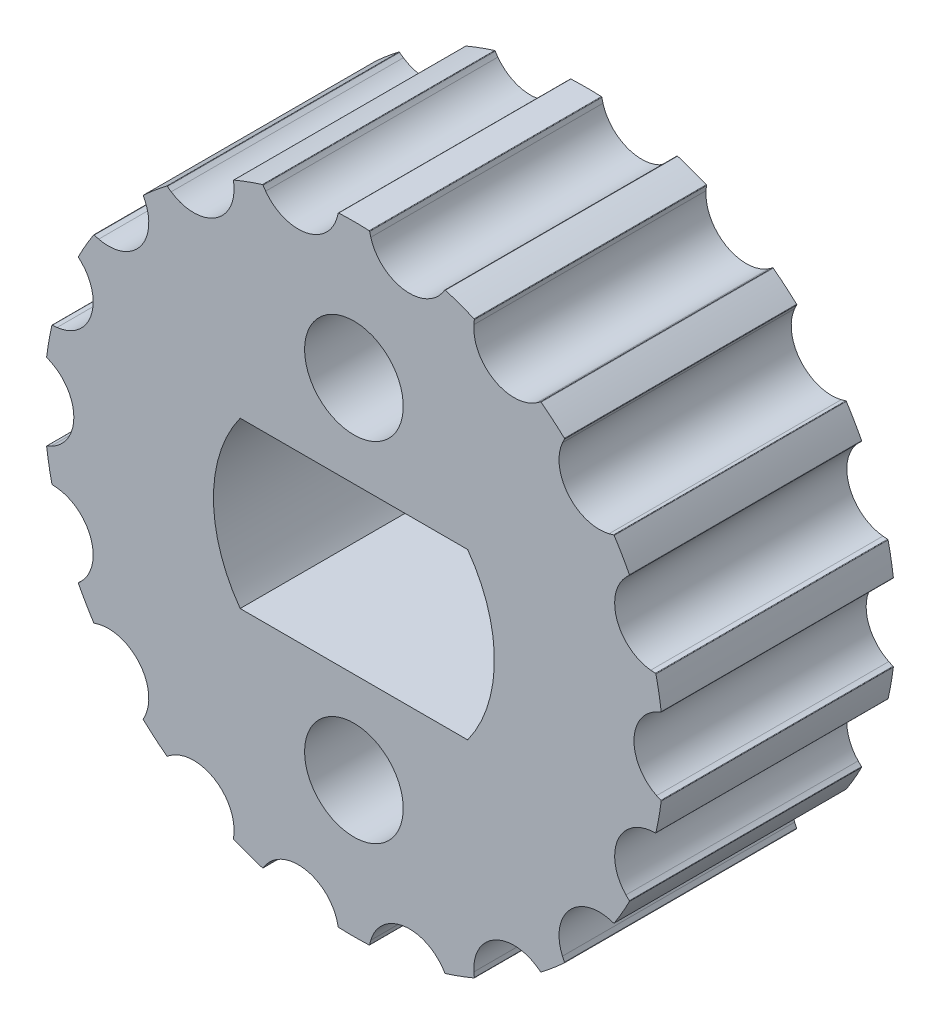
SolidWorks part; units mm, degrees
ref_plane "Face" through (0, 0, 0) normal (0, 0, 1) x (1, 0, 0)
ref_plane "Dessus" through (0, 0, 0) normal (0, 1, 0) x (1, 0, 0)
ref_plane "Droite" through (0, 0, 0) normal (1, 0, 0) x (0, 0, -1)
sketch "Esquisse1" plane through (0, 0, 0) normal (0, 0, 1) x (1, 0, 0)
  line L0 (0, 0) -> (-0.9949, 5.6425) construction
  line L1 (0, 0) -> (0.9949, 5.6425) construction
  line L2 (-1.1018, 6.2486) -> (-0.9949, 5.6425) construction
  line L3 (1.1018, 6.2486) -> (0.9949, 5.6425) construction
  line L4 (-1.3861, 5.5594) -> (0, 0) construction
  line L5 (0, 0) -> (0, 6.345) construction
  line L6 (-0.8378, 4.7517) -> (0, 0)
  line L7 (0, 0) -> (0.8378, 4.7517)
  arc A0 (-0.9949, 5.6425) -> (0.9949, 5.6425) centre (0, 0) cw construction
  arc A1 (1.1018, 6.2486) -> (-1.1018, 6.2486) centre (0, 0) ccw construction
  arc A2 (0.9508, 5.3924) -> (-0.9508, 5.3924) centre (0, 0) ccw construction
  arc A3 (-0.9949, 5.6425) -> (-1.3861, 5.5594) centre (0, 0) ccw construction
  arc A4 (-0.9508, 5.3924) -> (-1.3247, 5.3129) centre (0, 0) ccw construction
  arc A5 (-0.8622, 4.8895) -> (-0.4253, 5.2823) centre (-0.9585, 5.4361) ccw construction
  arc A6 (-0.4253, 5.2823) -> (-0.4082, 5.3505) centre (-1.3861, 5.5594) ccw construction
  arc A7 (0.9585, 5.4361) -> (-0.9585, 5.4361) centre (0, 0) ccw construction
  arc A8 (-0.4082, 5.3505) -> (-0.2688, 5.469) centre (-0.2615, 5.3192) cw construction
  arc A9 (-0.2688, 5.469) -> (0.2688, 5.469) centre (0, 0) cw construction
  arc A10 (0.4082, 5.3505) -> (0.2688, 5.469) centre (0.2615, 5.3192) ccw construction
  arc A11 (0.4253, 5.2823) -> (0.4082, 5.3505) centre (1.3861, 5.5594) cw construction
  arc A12 (0.8622, 4.8895) -> (0.4253, 5.2823) centre (0.9585, 5.4361) cw construction
  arc A13 (-0.8378, 4.7517) -> (-0.2907, 5.2435) centre (-0.9585, 5.4361) ccw
  arc A14 (-0.2907, 5.2435) -> (-0.2713, 5.3212) centre (-1.3861, 5.5594) ccw
  arc A15 (-0.2713, 5.3212) -> (-0.262, 5.3291) centre (-0.2615, 5.3192) cw
  arc A16 (-0.262, 5.3291) -> (0.262, 5.3291) centre (0, 0) cw
  arc A17 (0.2713, 5.3212) -> (0.262, 5.3291) centre (0.2615, 5.3192) ccw
  arc A18 (0.2907, 5.2435) -> (0.2713, 5.3212) centre (1.3861, 5.5594) cw
  arc A19 (0.8378, 4.7517) -> (0.2907, 5.2435) centre (0.9585, 5.4361) cw
  dimension "D2" = 0.254
  dimension "D3" = 0.555
  dimension "D4" = 2
  dimension "D5" = 0.4
  dimension "D6" = 1.38
  dimension "D7" = 0.15
  dimension "D8" = 1
  dimension "D9" = 0.14
  dimension "D1" = 20
extrude "Boss.-Extru.1" add sketch "Esquisse1" along normal blind 4
pattern_circular "Répétition circulaire2" count 18 over 360 about axis through (0, 0, 0) along (0, 0, 1) of "Boss.-Extru.1"
sketch "Esquisse2" plane through (0, 0, 4) normal (0, 0, 1) x (1, 0, 0)
  circle A0 centre (0, 0) radius 5 construction
  circle A1 centre (0, 0) radius 1
  dimension "D1" = 2
  dimension "D2" = 10
extrude "Enlèv. mat.-Extru.1" cut sketch "Esquisse2" against normal through all
sketch "Esquisse3" plane through (0, 0, 4) normal (0, 0, 1) x (1, 0, 0)
  circle A0 centre (0, 0) radius 5.3356 construction
sketch "Esquisse5" plane through (0, 0, 0) normal (0, 0, -1) x (-1, 0, 0)
  line L4 (-1.9596, -1.42) -> (1.9596, -1.42)
  line L5 (1.9596, 1.42) -> (-1.9596, 1.42)
  line L6 (-1.9596, -1.42) -> (1.9596, -1.42)
  line L7 (1.9596, 1.42) -> (-1.9596, 1.42)
  arc A4 (-1.9596, 1.42) -> (-1.9596, -1.42) centre (0, 0) ccw
  arc A5 (1.9596, -1.42) -> (1.9596, 1.42) centre (0, 0) ccw
  arc A6 (-1.9596, 1.42) -> (-1.9596, -1.42) centre (0, 0) ccw
  arc A7 (1.9596, -1.42) -> (1.9596, 1.42) centre (0, 0) ccw
  dimension "D1" = 0.08
extrude "Enlèv. mat.-Extru.2" cut sketch "Esquisse5" against normal through all
sketch "Esquisse6" plane through (0, 0, 0) normal (0, 0, -1) x (-1, 0, 0)
  line L0 (0, 3) -> (0, -3) construction
  circle A0 centre (0, 3) radius 0.85
  circle A1 centre (0, -3) radius 0.85
  point P2 (0, 0)
  dimension "D1" = 1.7
  dimension "D2" = 6
extrude "Enlèv. mat.-Extru.3" cut sketch "Esquisse6" against normal through all
